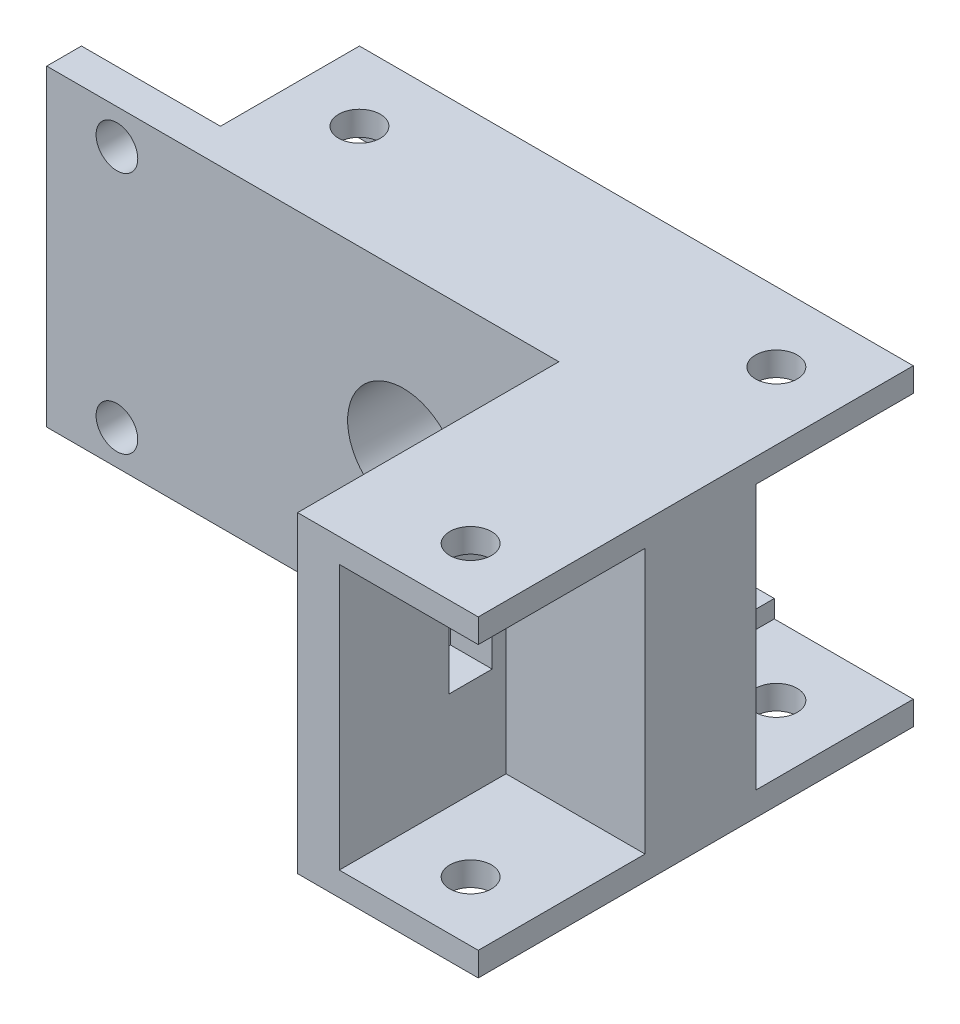
SolidWorks part; units mm, degrees
ref_plane "Front Plane" through (0, 0, 0) normal (0, 0, 1) x (1, 0, 0)
ref_plane "Top Plane" through (0, 0, 0) normal (0, 1, 0) x (1, 0, 0)
ref_plane "Right Plane" through (0, 0, 0) normal (1, 0, 0) x (0, 0, -1)
sketch "Sketch1" plane through (0, 0, 0) normal (0, 0, 1) x (1, 0, 0)
  line L1 (0, 0) -> (36.85, 0)
  line L2 (0, 0) -> (0, 22.5)
  line L3 (0, 22.5) -> (36.85, 22.5)
  line L4 (36.85, 0) -> (36.85, 22.5)
  dimension "D1" = 36.85
  dimension "D2" = 22.5
extrude "Boss-Extrude1" add sketch "Sketch1" along normal blind 2.5
sketch "Sketch2" plane through (36.85, 0, 0) normal (1, 0, 0) x (0, 0, -1)
  line L1 (0, 0) -> (-21.3, 0)
  line L2 (0, 0) -> (0, 22.5)
  line L3 (0, 22.5) -> (-21.3, 22.5)
  line L4 (-21.3, 0) -> (-21.3, 22.5)
  dimension "D1" = 22.5
  dimension "D2" = 21.3
extrude "Boss-Extrude2" add sketch "Sketch2" along normal blind 3
sketch "Sketch3" plane through (39.85, 0, 0) normal (1, 0, 0) x (0, 0, -1)
  line L0 (-21.3, 22.5) -> (-21.3, 0) construction
  line L1 (0, 0) -> (-21.3, 0)
  line L2 (0, 0) -> (0, 3)
  line L3 (0, 3) -> (-21.3, 3)
  line L4 (-21.3, 0) -> (-21.3, 3)
  dimension "D1" = 3
extrude "Boss-Extrude3" add sketch "Sketch3" along normal blind 10
sketch "Sketch4" plane through (0, 0, 0) normal (0, 0, -1) x (-1, 0, 0)
  line L1 (0, 0) -> (-49.85, 0)
  line L2 (0, 0) -> (0, 3)
  line L3 (0, 3) -> (-49.85, 3)
  line L4 (-49.85, 0) -> (-49.85, 3)
extrude "Boss-Extrude4" add sketch "Sketch4" along normal blind 10
sketch "Sketch8" plane through (39.85, 0, 0) normal (1, 0, 0) x (0, 0, -1)
  line L0 (-21.3, 22.5) -> (-21.3, 3) construction
  line L1 (-13.4, 13.75) -> (-10.3, 13.75)
  line L2 (-13.4, 13.75) -> (-13.4, 8.75)
  line L3 (-13.4, 8.75) -> (-10.3, 8.75)
  line L4 (-10.3, 13.75) -> (-10.3, 8.75)
  line L5 (-21.3, 0) -> (-2.5, 0) construction
  dimension "D1" = 3.1
  dimension "D2" = 5
  dimension "D3" = 7.9
  dimension "D4" = 8.75
extrude "Cut-Extrude1" cut sketch "Sketch8" against normal blind 5
sketch "Sketch9" plane through (0, 0, 2.5) normal (0, 0, 1) x (1, 0, 0)
  line L0 (36.85, 0) -> (36.85, 22.5) construction
  line L1 (0, 0) -> (36.85, 0) construction
  circle A0 centre (25.65, 11.25) radius 4
  circle A1 centre (5.05, 20) radius 1.5
  circle A2 centre (5.05, 2.5) radius 1.5
  dimension "D1" = 8
  dimension "D5" = 3
  dimension "D6" = 3
  dimension "D2" = 11.2
  dimension "D3" = 31.8
  dimension "D4" = 17.5
  dimension "D7" = 2.5
  dimension "D8" = 11.25
extrude "Cut-Extrude2" cut sketch "Sketch9" against normal blind 25
sketch "Sketch11" plane through (0, 0, -10) normal (0, 0, -1) x (-1, 0, 0)
  line L0 (-6.4642, 3) -> (-39.85, 3) construction
  line L1 (0, 0) -> (-10, 0)
  line L2 (0, 0) -> (0, 3)
  line L3 (0, 3) -> (-10, 3)
  line L4 (-10, 0) -> (-10, 3)
  dimension "D1" = 10
extrude "Cut-Extrude3" cut sketch "Sketch11" against normal blind 10
sketch "Sketch12" plane through (0, 3, 0) normal (0, 1, 0) x (1, 0, 0)
  line L0 (10, 0) -> (10, 10) construction
  line L1 (49.85, -21.3) -> (39.85, -21.3) construction
  line L2 (10, 10) -> (49.85, 10) construction
  circle A0 centre (15, 5) radius 1.5
  circle A1 centre (45, 5) radius 1.5
  circle A2 centre (45, -17) radius 1.5
  dimension "D1" = 3
  dimension "D2" = 30
  dimension "D3" = 22
  dimension "D4" = 5
  dimension "D5" = 5
extrude "Cut-Extrude4" cut sketch "Sketch12" against normal blind 10
sketch "Sketch14" plane through (0, 3, 0) normal (0, 1, 0) x (1, 0, 0)
  line L0 (10, 10) -> (49.85, 10) construction
  line L1 (20, 10) -> (32.5, 10)
  line L2 (20, 10) -> (20, 0)
  line L3 (20, 0) -> (32.5, 0)
  line L4 (32.5, 10) -> (32.5, 0)
  line L5 (10, 0) -> (39.85, 0) construction
  line L6 (39.85, 0) -> (39.85, -21.3) construction
  line L7 (39.85, -1.3) -> (49.85, -1.3)
  line L8 (39.85, -1.3) -> (39.85, -9.3)
  line L9 (39.85, -9.3) -> (49.85, -9.3)
  line L10 (49.85, -1.3) -> (49.85, -9.3)
  line L11 (49.85, 10) -> (49.85, -21.3) construction
  line L12 (10, 0) -> (10, 10) construction
  line L13 (49.85, -21.3) -> (39.85, -21.3) construction
  dimension "D1" = 12.5
  dimension "D2" = 10
  dimension "D3" = 8
  dimension "D4" = 12
extrude "Boss-Extrude8" add sketch "Sketch14" along normal up to vertex (19.5 mm away)
sketch "Sketch13" plane through (0, 22.5, 0) normal (0, 1, 0) x (1, 0, 0)
  line L0 (49.85, 10) -> (49.85, -1.3) construction
  line L1 (10, 10) -> (49.85, 10)
  line L2 (10, 10) -> (10, 0)
  line L3 (10, 0) -> (39.85, 0)
  line L4 (49.85, 10) -> (49.85, 0)
  line L7 (49.85, 0) -> (49.85, -21.3)
  line L8 (49.85, -21.3) -> (39.85, -21.3)
  line L9 (39.85, 0) -> (39.85, -21.3)
  circle A0 centre (15, 5) radius 1.5
  circle A1 centre (45, 5) radius 1.5
  circle A2 centre (45, -17) radius 1.5
extrude "Boss-Extrude7" add sketch "Sketch13" against normal blind 3
sketch "Sketch15" plane through (0, 0, 2.5) normal (0, 0, 1) x (1, 0, 0)
  circle A0 centre (25.65, 11.25) radius 4
extrude "Cut-Extrude5" cut sketch "Sketch15" against normal blind 43
sketch "Sketch16" plane through (0, 19.5, 0) normal (0, -1, 0) x (1, 0, 0)
  line L0 (10, 0) -> (10, -10) construction
  line L1 (10, -2.75) -> (20, -2.75)
  line L2 (10, -2.75) -> (10, -7.25)
  line L3 (10, -7.25) -> (20, -7.25)
  line L4 (20, -2.75) -> (20, -7.25)
  line L5 (49.85, -10) -> (10, -10) construction
  dimension "D1" = 10
  dimension "D2" = 4.5
  dimension "D3" = 2.75
extrude "Cut-Extrude6" cut sketch "Sketch16" against normal blind 1.25 and the other way blind 17.7525
sketch "Sketch17" plane through (49.85, 0, 0) normal (1, 0, 0) x (0, 0, -1)
  line L0 (-21.3, 22.5) -> (10, 22.5) construction
  line L1 (-23.4313, 20.775) -> (-9.3, 20.775)
  line L2 (-23.4313, 20.775) -> (-23.4313, 1.725)
  line L3 (-23.4313, 1.725) -> (-9.3, 1.725)
  line L4 (11.9346, 20.775) -> (11.9346, 1.725)
  line L7 (-9.3, 20.775) -> (-9.3, 1.725)
  line L8 (-1.3, 20.775) -> (-1.3, 1.725)
  line L9 (-9.3, 19.5) -> (-9.3, 3) construction
  line L10 (-1.3, 19.5) -> (-1.3, 3) construction
  line L11 (-1.3, 1.725) -> (11.9346, 1.725)
  line L12 (-1.3, 20.775) -> (11.9346, 20.775)
  dimension "D1" = 19.05
  dimension "D2" = 1.725
extrude "Cut-Extrude7" cut sketch "Sketch17" against normal up to vertex (10 mm away)
equation "\"D2@Sketch2\"=18.8+2.5"
